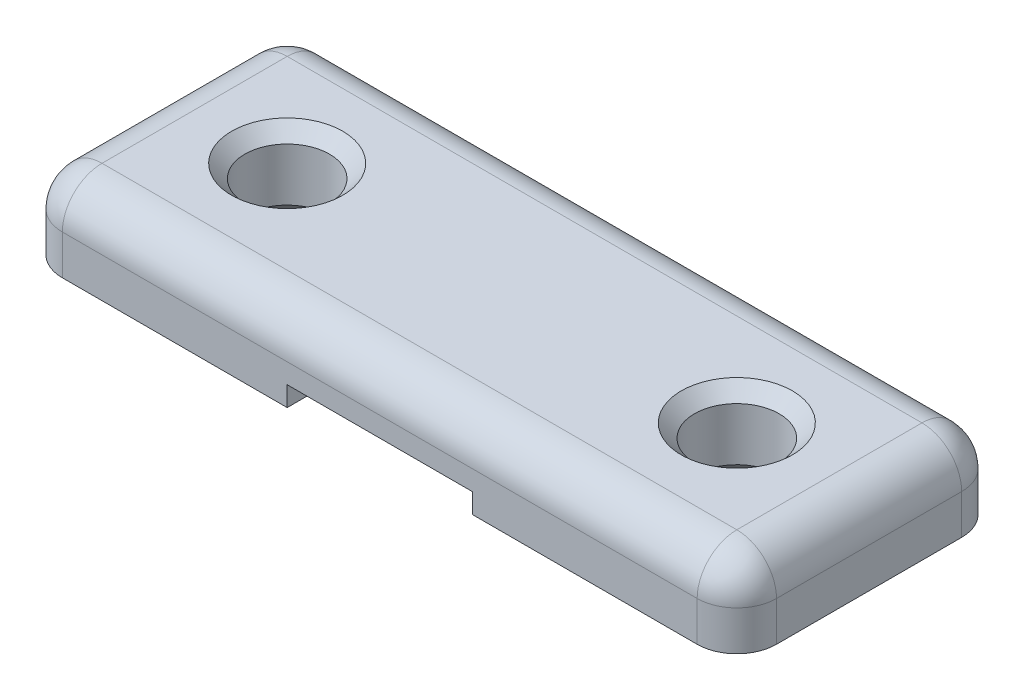
SolidWorks part; units mm, degrees
ref_plane "Спереди" through (0, 0, 0) normal (0, 0, 1) x (1, 0, 0)
ref_plane "Сверху" through (0, 0, 0) normal (0, 1, 0) x (1, 0, 0)
ref_plane "Справа" through (0, 0, 0) normal (1, 0, 0) x (0, 0, -1)
sketch "Эскиз1" plane through (0, 0, 0) normal (0, 1, 0) x (1, 0, 0)
  line L0 (-25.7727, 0) -> (59.6455, 0) construction
  line L1 (-13.5, -5) -> (13.5, -5)
  line L2 (-13.5, -5) -> (-13.5, 5)
  line L3 (-13.5, 5) -> (13.5, 5)
  line L4 (13.5, -5) -> (13.5, 5)
  line L5 (-13.5, -5) -> (13.5, 5) construction
  line L6 (-13.5, 5) -> (13.5, -5) construction
  circle A0 centre (-8.5, 0) radius 1.6
  circle A1 centre (8.5, 0) radius 1.6
  point P0 (0, 0)
  dimension "D5" = 3.2
  dimension "D1" = 27
  dimension "D2" = 10
  dimension "D3" = 5
  dimension "D4" = 5
extrude "Бобышка-Вытянуть1" add sketch "Эскиз1" along normal blind 3
sketch "Эскиз2" plane through (0, 0, 0) normal (1, 0, 0) x (0, 0, -1)
  line L0 (0, 3.442) -> (0, -0.9238) construction
  line L1 (-5, 0) -> (5, 0) construction
  line L2 (-2.1549, 0.75) -> (1.4366, 0.75) construction
  line L3 (-4.7433, 0.75) -> (-5, 0.75)
  line L4 (-5, 3) -> (-5, 0) construction
  line L5 (-3.2567, 0.75) -> (-2.7433, 0.75)
  line L6 (-1.2567, 0.75) -> (-0.7433, 0.75)
  line L7 (0.7433, 0.75) -> (1.2567, 0.75)
  line L8 (2.7433, 0.75) -> (3.2567, 0.75)
  line L9 (4.7433, 0.75) -> (5, 0.75)
  line L10 (5, 3) -> (5, 0) construction
  line L11 (5, 0.75) -> (5, 0)
  line L12 (5, 0) -> (-5, 0)
  line L13 (-5, 0) -> (-5, 0.75)
  arc A0 (-0.5051, 0.3182) -> (0.5051, 0.3182) centre (0, 0.56) ccw
  arc A1 (-0.5946, 0.6196) -> (-0.5051, 0.3182) centre (0.3969, 0.75) ccw
  arc A2 (0.5051, 0.3182) -> (0.5946, 0.6196) centre (-0.3969, 0.75) ccw
  arc A3 (-0.5946, 0.6196) -> (-0.7433, 0.75) centre (-0.7433, 0.6) ccw
  arc A4 (0.7433, 0.75) -> (0.5946, 0.6196) centre (0.7433, 0.6) ccw
  arc A5 (1.4054, 0.6196) -> (1.2567, 0.75) centre (1.2567, 0.6) ccw
  arc A6 (1.4054, 0.6196) -> (1.4949, 0.3182) centre (2.3969, 0.75) ccw
  arc A7 (1.4949, 0.3182) -> (2.5051, 0.3182) centre (2, 0.56) ccw
  arc A8 (2.5051, 0.3182) -> (2.5946, 0.6196) centre (1.6031, 0.75) ccw
  arc A9 (2.7433, 0.75) -> (2.5946, 0.6196) centre (2.7433, 0.6) ccw
  arc A10 (3.4054, 0.6196) -> (3.2567, 0.75) centre (3.2567, 0.6) ccw
  arc A11 (3.4054, 0.6196) -> (3.4949, 0.3182) centre (4.3969, 0.75) ccw
  arc A12 (3.4949, 0.3182) -> (4.5051, 0.3182) centre (4, 0.56) ccw
  arc A13 (4.5051, 0.3182) -> (4.5946, 0.6196) centre (3.6031, 0.75) ccw
  arc A14 (4.7433, 0.75) -> (4.5946, 0.6196) centre (4.7433, 0.6) ccw
  arc A15 (-2.5946, 0.6196) -> (-2.7433, 0.75) centre (-2.7433, 0.6) ccw
  arc A16 (-2.5946, 0.6196) -> (-2.5051, 0.3182) centre (-1.6031, 0.75) ccw
  arc A17 (-2.5051, 0.3182) -> (-1.4949, 0.3182) centre (-2, 0.56) ccw
  arc A18 (-1.4949, 0.3182) -> (-1.4054, 0.6196) centre (-2.3969, 0.75) ccw
  arc A19 (-1.2567, 0.75) -> (-1.4054, 0.6196) centre (-1.2567, 0.6) ccw
  arc A20 (-4.5946, 0.6196) -> (-4.7433, 0.75) centre (-4.7433, 0.6) ccw
  arc A21 (-4.5946, 0.6196) -> (-4.5051, 0.3182) centre (-3.6031, 0.75) ccw
  arc A22 (-4.5051, 0.3182) -> (-3.4949, 0.3182) centre (-4, 0.56) ccw
  arc A23 (-3.4949, 0.3182) -> (-3.4054, 0.6196) centre (-4.3969, 0.75) ccw
  arc A24 (-3.2567, 0.75) -> (-3.4054, 0.6196) centre (-3.2567, 0.6) ccw
  dimension "D1" = 1.12
  dimension "D3" = 2
  dimension "D4" = 3
  dimension "D5" = 0.3
  dimension "D2" = 0.75
  dimension "D6" = 3
extrude "Вырез-Вытянуть1" cut sketch "Эскиз2" against normal mid plane 7 contours L5 A24 A23 A22 L12 A17 A16 A15 | A22 A21 A20 L3 L13 L12 | L6 A19 A18 A17 L12 A0 A1 A3 | A7 A6 A5 L7 A4 A2 A0 L12 | A12 A11 A10 L8 A9 A8 A7 L12 | L9 A14 A13 A12 L12 L11
fillet "Скругление1" radius 1.5 8 edges at (-13.5, 1.5, -5) (-13.5, 1.5, 5) (13.5, 1.5, 5) (13.5, 1.5, -5) (13.5, 3, 0) (0, 3, 5) (-13.5, 3, 0) (0, 3, -5)
chamfer "Фаска1" distance 0.5 angle 45 4 edges at (8.5, 3, 1.6) (-8.5, 3, 1.6) (-8.5, 0, 1.6) (8.5, 0, 1.6)
